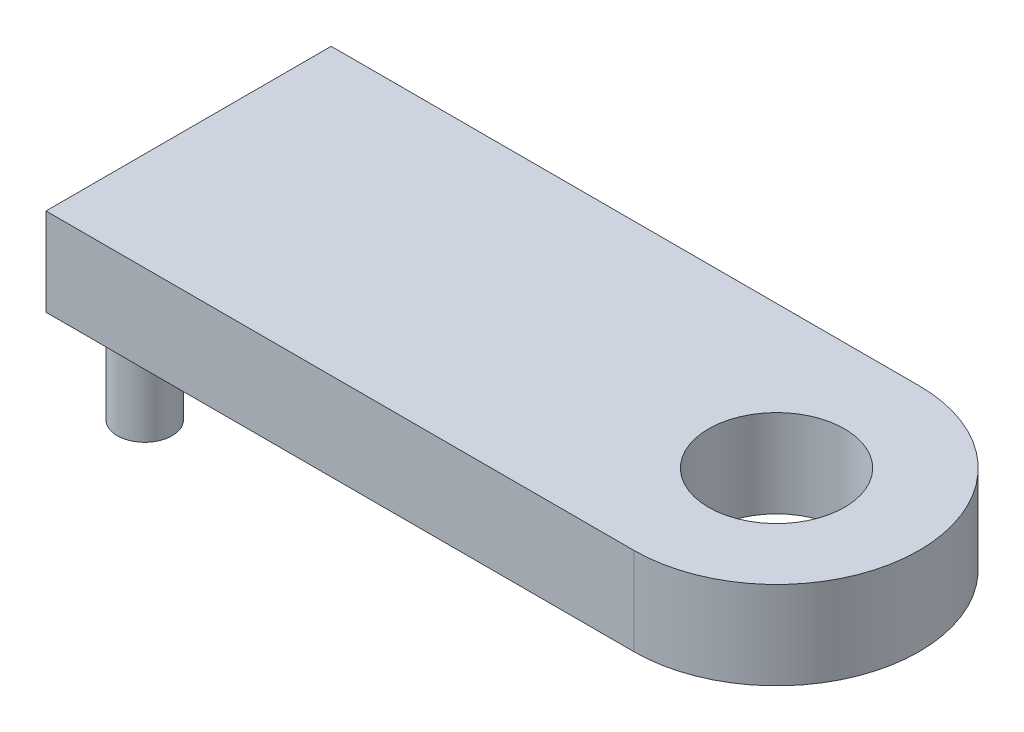
SolidWorks part; units mm, degrees
material "ABS"
ref_plane "Front Plane" through (0, 0, 0) normal (0, 0, 1) x (1, 0, 0)
ref_plane "Top Plane" through (0, 0, 0) normal (0, 1, 0) x (1, 0, 0)
ref_plane "Right Plane" through (0, 0, 0) normal (1, 0, 0) x (0, 0, -1)
ref_plane "Y+23_10" through (0, 23.1, 0) normal (0, 1, 0) x (1, 0, 0)
sketch "Sketch1" plane through (0, 23.1, 0) normal (0, 1, 0) x (1, 0, 0)
  line L0 (5.5, 6.5) -> (-21.3, 6.5)
  line L1 (-21.3, 6.5) -> (-21.3, -6.5)
  line L2 (-21.3, -6.5) -> (5.5, -6.5)
  arc A0 (5.5, -6.5) -> (5.5, 6.5) centre (5.5, 0) ccw
extrude "Boss-Extrude1" add sketch "Sketch1" along normal blind 4
sketch "Sketch2" plane through (0, 23.1, 0) normal (0, 1, 0) x (1, 0, 0)
  circle A0 centre (5.5, 0) radius 3.1
extrude "Cut-Extrude2" cut sketch "Sketch2" along normal blind 4
ref_plane "Y+19_10" through (0, 19.1, 0) normal (0, 1, 0) x (1, 0, 0)
sketch "Sketch3" plane through (0, 19.1, 0) normal (0, 1, 0) x (1, 0, 0)
  circle A0 centre (-18.8, -4.5) radius 1.25
  circle A1 centre (-18.8, 4.5) radius 1.25
extrude "Boss-Extrude2" add sketch "Sketch3" along normal blind 4
